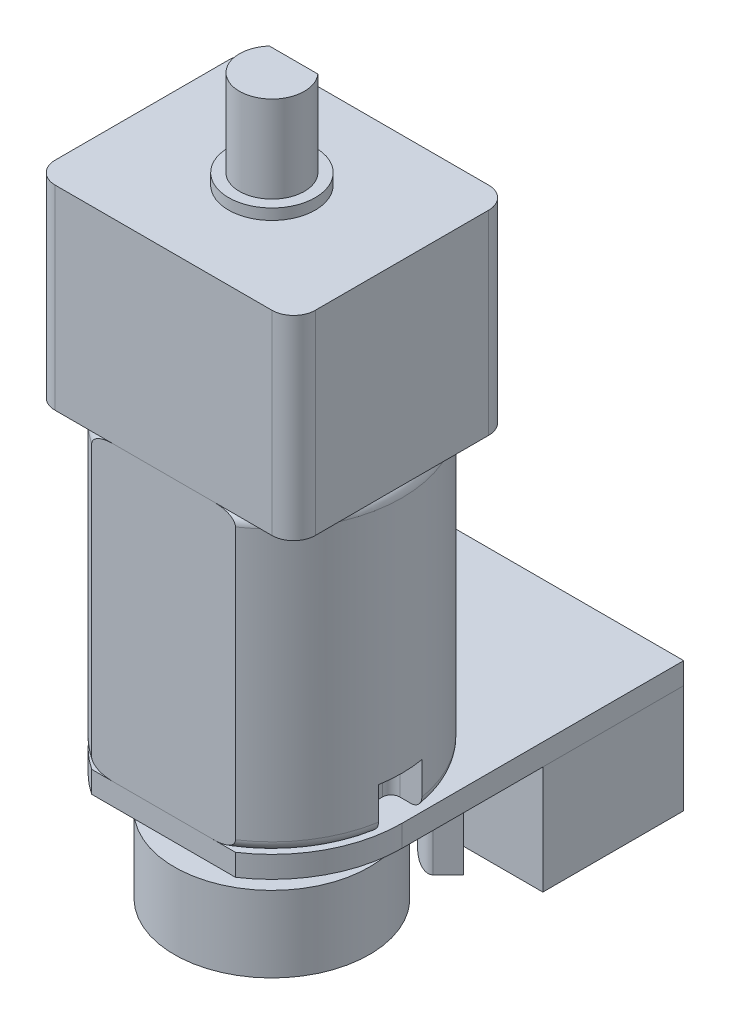
SolidWorks part; units mm, degrees
ref_plane "Спереди" through (0, 0, 0) normal (0, 0, 1) x (1, 0, 0)
ref_plane "Сверху" through (0, 0, 0) normal (0, 1, 0) x (1, 0, 0)
ref_plane "Справа" through (0, 0, 0) normal (1, 0, 0) x (0, 0, -1)
sketch "Эскиз1" plane through (0, 0, 0) normal (0, 1, 0) x (1, 0, 0)
  line L0 (0, -5) -> (0, 5)
  line L1 (-3.3166, 5) -> (3.3166, 5)
  line L2 (-3.3166, -5) -> (3.3166, -5)
  circle A0 centre (0, 0) radius 6
  point P6 (0, 0)
  point P8 (0, 5)
  point P12 (0, -5)
extrude "Бобышка-Вытянуть1" add sketch "Эскиз1" along normal blind 13.5 contours L1 A0 L2 L0 | L2 A0 L1 L0
sketch "Эскиз2" plane through (0, 13.5, 0) normal (0, 1, 0) x (1, 0, 0)
  line L1 (-6, 5) -> (6, 5)
  line L2 (-6, 5) -> (-6, -5)
  line L3 (-6, -5) -> (6, -5)
  line L4 (6, 5) -> (6, -5)
extrude "Бобышка-Вытянуть2" add sketch "Эскиз2" along normal blind 9 separate body
sketch "Эскиз3" plane through (0, 22.5, 0) normal (0, 1, 0) x (1, 0, 0)
  circle A0 centre (0, 0) radius 2
extrude "Бобышка-Вытянуть3" add sketch "Эскиз3" along normal blind 0.5
sketch "Эскиз4" plane through (0, 23, 0) normal (0, 1, 0) x (1, 0, 0)
  line L0 (0, -1.5) -> (0, 1)
  line L1 (-1.118, 1) -> (1.118, 1)
  circle A0 centre (0, 0) radius 1.5
  point P8 (0, 1)
extrude "Бобышка-Вытянуть4" add sketch "Эскиз4" along normal blind 4 separate body contours L1 A0 L0 | L0 A0 L1
fillet "Скругление1" radius 1 4 edges at (6, 18, 5) (-6, 18, 5) (-6, 18, -5) (6, 18, -5)
fillet "Скругление2" radius 0.5 4 edges at (-6, 0, 0) (-6, 13.5, 0) (6, 0, 0) (6, 13.5, 0)
sketch "Эскиз5" plane through (0, 0, 0) normal (0, -1, 0) x (1, 0, 0)
  circle A0 centre (0, 0) radius 2.5
extrude "Бобышка-Вытянуть5" add sketch "Эскиз5" along normal blind 1
sketch "Эскиз6" plane through (0, 0, 0) normal (0, -1, 0) x (1, 0, 0)
  line L0 (0, 5) -> (0, 0) construction
  line L1 (-2.2913, 5) -> (2.2913, 5) construction
  line L2 (6, 0) -> (6, 1)
  line L3 (6, 4) -> (6, -4) construction
  line L4 (6, 1) -> (4.5, 1)
  line L5 (4.5, 1) -> (4.5, -1)
  line L6 (4.5, -1) -> (6, -1)
  line L7 (6, -1) -> (6, 0)
  line L8 (-4.5, -1) -> (-6, -1)
  line L9 (-4.5, 1) -> (-4.5, -1)
  line L10 (-6, 1) -> (-4.5, 1)
  line L11 (-6, 0) -> (-6, 1)
  line L12 (-6, -1) -> (-6, 0)
  arc A0 (3.3166, -5) -> (3.3166, 5) centre (0, 0) ccw construction
  point P20 (4.5, 0)
extrude "Вырез-Вытянуть1" cut sketch "Эскиз6" against normal blind 2
fillet "Скругление3" radius 0.4 6 edges at (-4.5, 1, -1) (-4.5, 1, 1) (-4.5, 2, 0) (4.5, 1, 1) (4.5, 1, -1) (4.5, 2, 0)
sketch "Эскиз7" plane through (0, 0, 0) normal (0, -1, 0) x (1, 0, 0)
  line L0 (4, 0) -> (-4, 0) construction
  line L1 (-4.25, 0) -> (-3.75, 0)
  line L7 (0, 0) -> (0, -5) construction
  line L8 (-2.2913, -5) -> (2.2913, -5) construction
  line L10 (-4.25, -0.75) -> (-4.25, 0.75)
  line L11 (-4.25, 0.75) -> (-3.75, 0.75)
  line L12 (-3.75, 0.75) -> (-3.75, -0.75)
  line L13 (-3.75, -0.75) -> (-4.25, -0.75)
  line L14 (-3.75, 0.75) -> (-4.25, 0.75)
  line L15 (-4.25, -0.75) -> (-3.75, -0.75)
  line L16 (-4.25, 0.75) -> (-3.75, 0.75)
  line L17 (-3.75, -0.75) -> (-4.25, -0.75)
  line L18 (-3.75, 0.75) -> (-4.25, 0.75)
  line L19 (-4.25, -0.75) -> (-3.75, -0.75)
  line L20 (4.25, -0.75) -> (3.75, -0.75)
  line L21 (3.75, 0.75) -> (4.25, 0.75)
  line L22 (3.75, -0.75) -> (4.25, -0.75)
  line L23 (4.25, 0.75) -> (3.75, 0.75)
  line L24 (4.25, -0.75) -> (3.75, -0.75)
  line L25 (3.75, 0.75) -> (4.25, 0.75)
  line L26 (3.75, -0.75) -> (4.25, -0.75)
  line L27 (3.75, 0.75) -> (3.75, -0.75)
  line L28 (4.25, 0.75) -> (3.75, 0.75)
  line L29 (4.25, -0.75) -> (4.25, 0.75)
  line L30 (4.25, 0) -> (3.75, 0)
  point P4 (-4, 0)
  point P7 (-4.25, 0)
  point P21 (4.25, 0)
  point P22 (4, 0)
extrude "Бобышка-Вытянуть6" add sketch "Эскиз7" along normal blind 2 contours L12 L11 L10 L1 | L13 L12 L1 L10 | L30 L29 L21 L27 | L29 L30 L27 L20
sketch "Эскиз8" plane through (4.25, 0, 0) normal (1, 0, 0) x (0, 0, -1)
  line L0 (0, -1.25) -> (0.75, -2) construction
  line L2 (0, -1.25) -> (-0.75, -2) construction
  circle A0 centre (0, -1.25) radius 0.25
  circle A2 centre (-0.375, -1.625) radius 0.375
  circle A3 centre (0.375, -1.625) radius 0.375
extrude "Вырез-Вытянуть2" cut sketch "Эскиз8" against normal through all both and the other way through all
sketch "Эскиз9" plane through (0, 0, 0) normal (0, -1, 0) x (1, 0, 0)
  line L1 (-6, 5) -> (6, 5)
  line L2 (-6, 5) -> (-6, -13)
  line L3 (-6, -13) -> (6, -13)
  line L4 (6, 5) -> (6, -13)
  line L5 (-4.25, 0.75) -> (-3.75, 0.75)
  line L6 (-4.25, 0.75) -> (-4.25, -0.75)
  line L7 (-4.25, -0.75) -> (-3.75, -0.75)
  line L8 (-3.75, 0.75) -> (-3.75, -0.75)
  line L9 (3.75, 0.75) -> (4.25, 0.75)
  line L10 (3.75, 0.75) -> (3.75, -0.75)
  line L11 (3.75, -0.75) -> (4.25, -0.75)
  line L12 (4.25, 0.75) -> (4.25, -0.75)
  circle A0 centre (0, 0) radius 2.5
extrude "Бобышка-Вытянуть8" add sketch "Эскиз9" along normal blind 1 separate body
sketch "Эскиз10" plane through (0, -1, 0) normal (0, -1, 0) x (1, 0, 0)
  circle A0 centre (0, 0) radius 0.5
extrude "Бобышка-Вытянуть10" add sketch "Эскиз10" along normal blind 5
sketch "Эскиз11" plane through (0, -6, 0) normal (0, -1, 0) x (1, 0, 0)
  circle A0 centre (0, 0) radius 4.5
  circle A1 centre (0, 0) radius 0.5
extrude "Бобышка-Вытянуть11" add sketch "Эскиз11" against normal blind 3.5 separate body
sketch "Эскиз12" plane through (0, -1, 0) normal (0, -1, 0) x (1, 0, 0)
  line L0 (0, 0) -> (-3.7123, -3.7123) construction
  line L1 (-3.7123, -3.7123) -> (0, -7.4246) construction
  line L2 (0, -7.4246) -> (3.7123, -3.7123) construction
  line L3 (3.7123, -3.7123) -> (0, 0) construction
  line L4 (-3.7123, -3.7123) -> (-2.6517, -4.773)
  line L5 (-2.6517, -4.773) -> (-3.3588, -5.4801)
  line L6 (-3.3588, -5.4801) -> (-5.4801, -3.3588)
  line L7 (-5.4801, -3.3588) -> (-4.773, -2.6517)
  line L8 (-4.773, -2.6517) -> (-3.7123, -3.7123)
  line L9 (0, 0) -> (0, -7.4246) construction
  line L10 (3.7123, -3.7123) -> (2.6517, -4.773)
  line L11 (4.773, -2.6517) -> (3.7123, -3.7123)
  line L12 (5.4801, -3.3588) -> (4.773, -2.6517)
  line L13 (3.3588, -5.4801) -> (5.4801, -3.3588)
  line L14 (2.6517, -4.773) -> (3.3588, -5.4801)
  circle A0 centre (0, 0) radius 5.25
  ellipse E0 centre (-3.7123, -3.7123) end of major axis (-4.773, -2.6517) minor radius 0.5
  ellipse E1 centre (3.7123, -3.7123) end of major axis (2.6517, -4.773) minor radius 0.5
extrude "Бобышка-Вытянуть12" add sketch "Эскиз12" along normal blind 3 separate body contours E0 L7 L6 L5 | L8 E0 L4 | A0 E0 | L12 E1 L14 L13 | E1 L11 L10 | E1 A0 | E1 A0 L11 | E1 L10 A0 | A0 E0 L8 | L4 E0 A0
sketch "Эскиз13" plane through (0, -1, 0) normal (0, -1, 0) x (1, 0, 0)
  line L0 (6, -13) -> (6, 5) construction
  line L1 (-6, -13) -> (6, -13)
  line L2 (-6, -13) -> (-6, -6.5)
  line L3 (-6, -6.5) -> (6, -6.5)
  line L4 (6, -13) -> (6, -6.5)
extrude "Бобышка-Вытянуть13" add sketch "Эскиз13" along normal blind 5 separate body
sketch "Эскиз14" plane through (0, 0, -13) normal (0, 0, -1) x (-1, 0, 0)
  line L0 (-6, -1) -> (-5, -1) construction
  line L1 (6, -1) -> (-6, -1) construction
  line L2 (-5, -1) -> (-5, -5)
  line L3 (-5, -5) -> (5, -5)
  line L4 (5, -5) -> (5, -2)
  line L5 (5, -2) -> (-5, -2)
extrude "Вырез-Вытянуть3" cut sketch "Эскиз14" against normal blind 5.5 contours L4 L5 L2 L3
sketch "Эскиз15" plane through (0, -1, 0) normal (0, -1, 0) x (1, 0, 0)
  line L0 (-6, 5) -> (6, 5)
  line L1 (-6, 0) -> (6, 0)
  line L2 (-6, 0) -> (-6, 6)
  line L3 (-6, 6) -> (6, 6)
  line L4 (6, 0) -> (6, 6)
  circle A0 centre (0, 0) radius 6
extrude "Вырез-Вытянуть4" cut sketch "Эскиз15" against normal blind 1 contours A0 L0 L2 | A0 L4 L0
